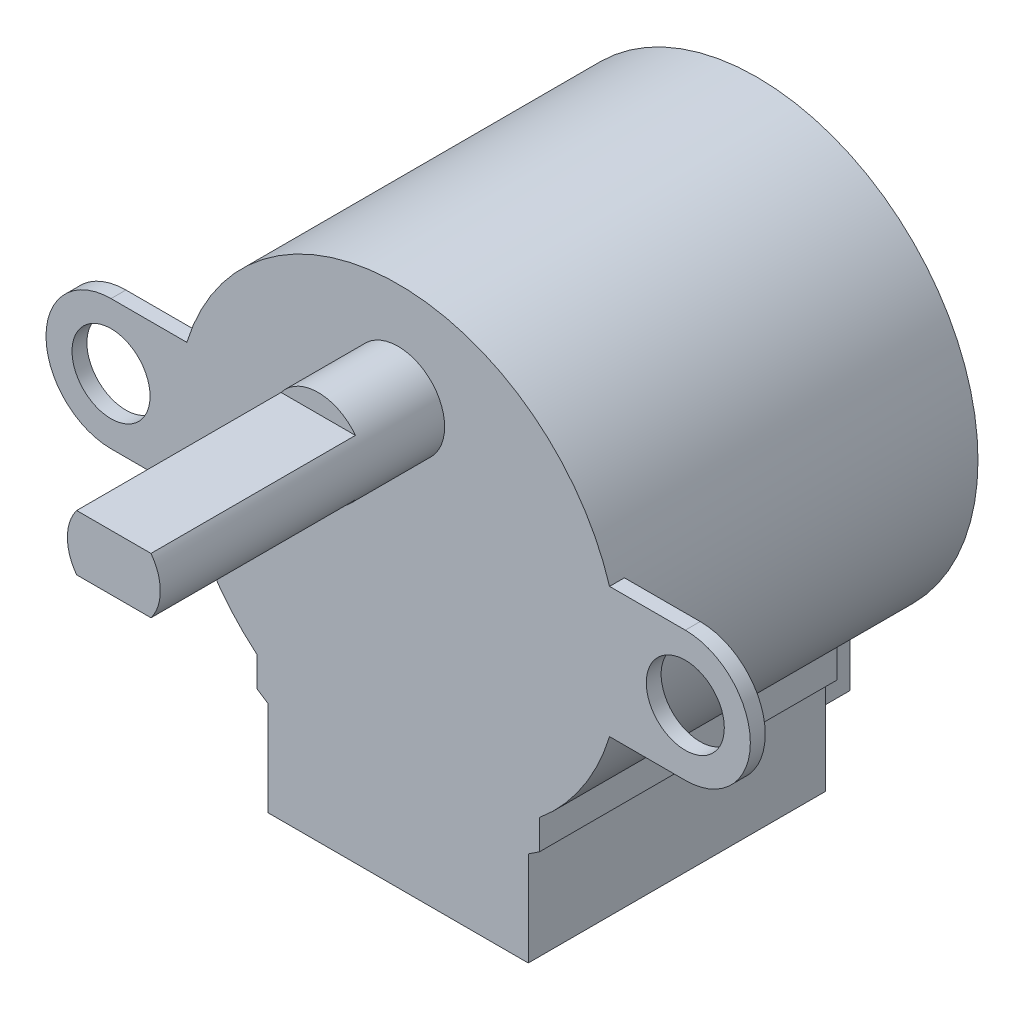
SolidWorks part; units mm, degrees
ref_plane "Front Plane" through (0, 0, 0) normal (0, 0, 1) x (1, 0, 0)
ref_plane "Top Plane" through (0, 0, 0) normal (0, 1, 0) x (1, 0, 0)
ref_plane "Right Plane" through (0, 0, 0) normal (1, 0, 0) x (0, 0, -1)
sketch "Sketch2" plane through (0, 0, 0) normal (0, 0, 1) x (1, 0, 0)
  line L1 (-5, -14.1986) -> (0, -14.1986)
  line L2 (-5, -14.1986) -> (-5, -10.7986)
  line L5 (5, -14.1986) -> (0, -14.1986)
  line L6 (5, -14.1986) -> (5, -10.7986)
  arc A0 (5, -10.7986) -> (-5, -10.7986) centre (0, 0) ccw
  dimension "D2" = 23.8
  dimension "D1" = 10
  dimension "D3" = 3.4
extrude "Housing Boss-Extrude1" add sketch "Sketch2" against normal blind 19.3
sketch "Sketch4" plane through (0, 0, 0) normal (0, 0, 1) x (1, 0, 0)
  line L0 (0, -16.2377) -> (-7, -16.2377)
  line L1 (0, -16.2377) -> (7, -16.2377)
  line L2 (7, -16.2377) -> (7, -11.1515)
  line L3 (-7, -16.2377) -> (-7, -11.1515)
  line L4 (7, -11.1515) -> (7.6, -10.757)
  line L5 (7.6, -10.757) -> (7.6, -9.157)
  line L6 (-7, -11.1515) -> (-7.6, -10.757)
  line L7 (-7.6, -10.757) -> (-7.6, -9.157)
  line L8 (-5, -10.7986) -> (-5, -14.1986)
  line L9 (-5, -14.1986) -> (5, -14.1986)
  line L10 (5, -14.1986) -> (5, -10.7986)
  arc A0 (5, -10.7986) -> (7.6, -9.157) centre (0, 0) ccw
  arc A1 (-7.6, -9.157) -> (-5, -10.7986) centre (0, 0) ccw
  dimension "D1" = 14
  dimension "D2" = 1.6
  dimension "D3" = 15.2
  dimension "D4" = 7.6
extrude "Plastic Sheilding Boss-Extrude2" add sketch "Sketch4" against normal blind 16
sketch "Sketch5" plane through (0, 0, 0) normal (0, 0, 1) x (1, 0, 0)
  line L0 (-26.4954, 0) -> (24.1149, 0) construction
  line L1 (-15.45, 3.5) -> (-11.3737, 3.5)
  line L2 (-15.45, -3.5) -> (-11.3737, -3.5)
  line L3 (15.45, 3.5) -> (11.3737, 3.5)
  line L4 (15.45, -3.5) -> (11.3737, -3.5)
  arc A0 (15.45, -3.5) -> (15.45, 3.5) centre (15.45, 0) ccw
  arc A1 (-15.45, 3.5) -> (-15.45, -3.5) centre (-15.45, 0) ccw
  arc A2 (11.3737, -3.5) -> (11.3737, 3.5) centre (0, 0) ccw
  arc A3 (7.6, -9.157) -> (-7.6, -9.157) centre (0, 0) ccw construction
  arc A4 (-11.3737, 3.5) -> (-11.3737, -3.5) centre (0, 0) ccw
  circle A5 centre (15.45, 0) radius 2.1
  circle A6 centre (-15.45, 0) radius 2.1
  dimension "D2" = 37.9
  dimension "D3" = 4.2
  dimension "D1" = 7
extrude "Mounting Brackets Boss-Extrude3" add sketch "Sketch5" against normal blind 0.8
sketch "Sketch6" plane through (0, 0, 0) normal (0, 0, 1) x (1, 0, 0)
  circle A0 centre (0, 6.5) radius 2.5
  dimension "D1" = 5
  dimension "D2" = 6.5
extrude "Shaft Boss-Extrude4" add sketch "Sketch6" along normal blind 15.3
sketch "Sketch7" plane through (0, 0, 15.3) normal (0, 0, 1) x (1, 0, 0)
  line L0 (-2, 8) -> (2, 8)
  line L1 (-2, 5) -> (2, 5)
  arc A0 (2, 8) -> (-2, 8) centre (0, 6.5) ccw
  circle A1 centre (0, 6.5) radius 2.5 construction
  arc A2 (-2, 5) -> (2, 5) centre (0, 6.5) ccw
  dimension "D1" = 3
extrude "Shaft EdgeCut-Extrude1" cut sketch "Sketch7" against normal blind 11
sketch "Sketch8" plane through (0, -16.2377, 0) normal (0, -1, 0) x (1, 0, 0)
  line L0 (-7, 0) -> (7, 0) construction
  line L1 (0, -2) -> (3.25, -2)
  line L3 (0, -3.2) -> (3.25, -3.2)
  line L4 (3.25, -2) -> (3.25, -3.2)
  line L5 (0, -2) -> (-3.25, -2)
  line L7 (0, -3.2) -> (-3.25, -3.2)
  line L8 (-3.25, -2) -> (-3.25, -3.2)
  dimension "D1" = 6.5
  dimension "D2" = 2
  dimension "D3" = 1.2
extrude "Cable Hole Cut-Extrude2" cut sketch "Sketch8" against normal blind 5
